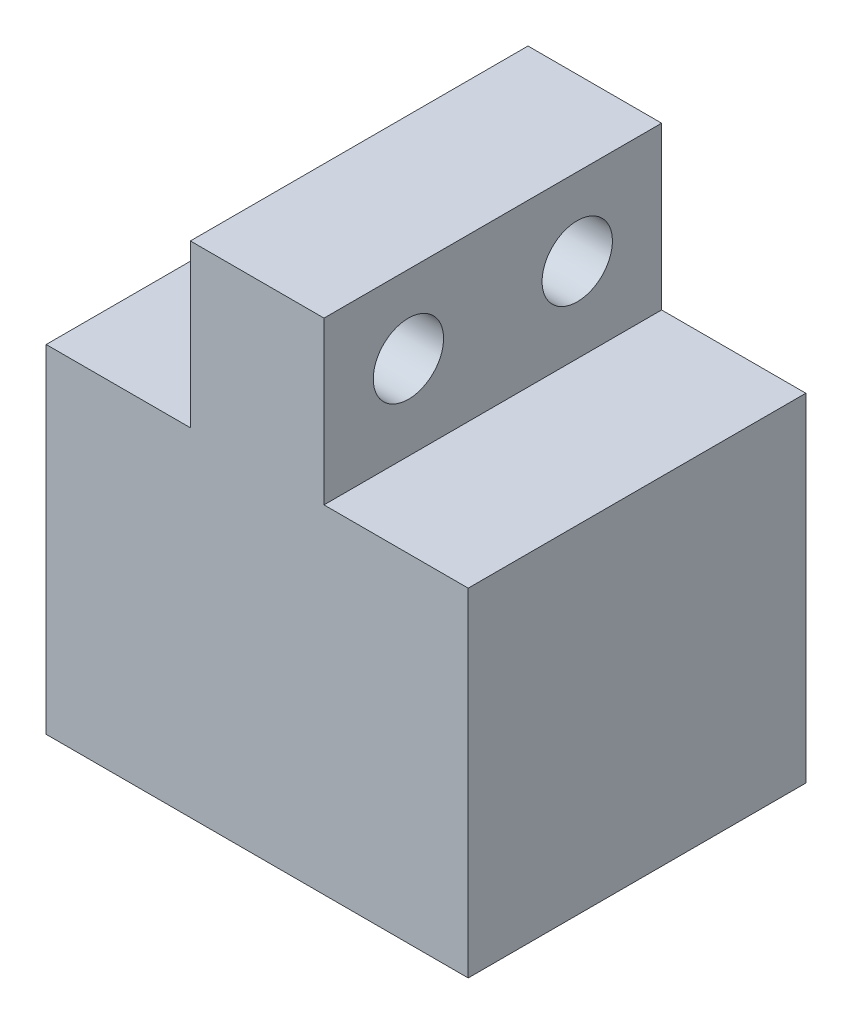
SolidWorks part; units mm, degrees
material "PLA"
ref_plane "Alzado" through (0, 0, 0) normal (0, 0, 1) x (1, 0, 0)
ref_plane "Planta" through (0, 0, 0) normal (0, 1, 0) x (1, 0, 0)
ref_plane "Vista lateral" through (0, 0, 0) normal (1, 0, 0) x (0, 0, -1)
sketch "Sketch1" plane through (0, 0, 0) normal (0, 0, 1) x (1, 0, 0)
  line L1 (0, 0) -> (15, 0)
  line L2 (0, 0) -> (0, 12)
  line L3 (0, 12) -> (15, 12)
  line L4 (15, 0) -> (15, 12)
  line L5 (5.125, 12) -> (9.875, 12)
  line L6 (5.125, 12) -> (5.125, 17.75)
  line L7 (5.125, 17.75) -> (9.875, 17.75)
  line L8 (9.875, 12) -> (9.875, 17.75)
  dimension "D1" = 12
  dimension "D2" = 15
  dimension "D3" = 4.75
  dimension "D4" = 5.125
  dimension "D5" = 5.75
extrude "Boss-Extrude1" add sketch "Sketch1" along normal blind 12 contours L3 L8 L7 L6 | L1 L4 L3 L2
sketch "Sketch2" plane through (5.125, 0, 0) normal (-1, 0, 0) x (0, 0, 1)
  line L0 (0, 12) -> (0, 17.75) construction
  line L1 (12, 12) -> (12, 17.75) construction
  line L2 (12, 12) -> (0, 12) construction
  line L3 (12, 12) -> (0, 12) construction
  circle A0 centre (3, 15) radius 1.25
  circle A1 centre (9, 15) radius 1.25
  dimension "D1" = 2.5
  dimension "D2" = 2.5
  dimension "D3" = 3
  dimension "D4" = 3
  dimension "D5" = 3
  dimension "D6" = 3
extrude "Cut-Extrude1" cut sketch "Sketch2" against normal blind 10
